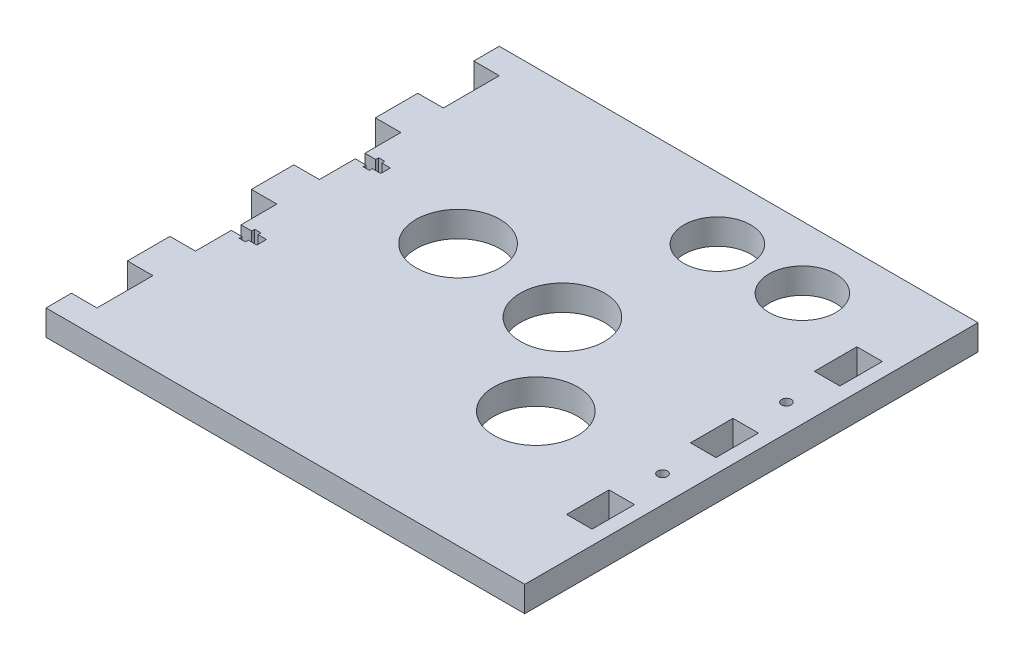
SolidWorks part; units mm, degrees
ref_plane "Front Plane" through (0, 0, 0) normal (0, 0, 1) x (1, 0, 0)
ref_plane "Top Plane" through (0, 0, 0) normal (0, 1, 0) x (1, 0, 0)
ref_plane "Right Plane" through (0, 0, 0) normal (1, 0, 0) x (0, 0, -1)
sketch "Sketch1" plane through (0, 0, 0) normal (0, 1, 0) x (1, 0, 0)
  line L1 (80, -80) -> (-80, -80)
  line L2 (80, -80) -> (80, 80)
  line L3 (80, 80) -> (-80, 80)
  line L4 (-80, -80) -> (-80, 80)
  line L5 (80, -80) -> (-80, 80) construction
  line L6 (80, 80) -> (-80, -80) construction
  point P0 (0, 0)
  dimension "D1" = 160
extrude "Boss-Extrude1" add sketch "Sketch1" along normal blind 9
sketch "Sketch2" plane through (0, 9, 0) normal (0, 1, 0) x (1, 0, 0)
  line L0 (-80, 80) -> (-80, -80) construction
  line L1 (-80, -7.5) -> (-89, -7.5)
  line L2 (-80, -7.5) -> (-80, 7.5)
  line L3 (-80, 7.5) -> (-89, 7.5)
  line L4 (-89, -7.5) -> (-89, 7.5)
  line L5 (-80, 0) -> (0, 0) construction
  line L6 (-80, 80) -> (-80, 51.25) construction
  line L7 (-80, 51.25) -> (-89, 51.25)
  line L8 (-80, 51.25) -> (-80, 36.25)
  line L9 (-80, 36.25) -> (-89, 36.25)
  line L10 (-89, 51.25) -> (-89, 36.25)
  line L11 (-80, -36.25) -> (-89, -36.25)
  line L12 (-80, -36.25) -> (-80, -51.25)
  line L13 (-80, -51.25) -> (-89, -51.25)
  line L14 (-89, -36.25) -> (-89, -51.25)
  line L15 (-80, 36.25) -> (-80, 7.5) construction
  line L16 (-80, -7.5) -> (-80, -36.25) construction
  line L17 (-80, -51.25) -> (-80, -80) construction
  line L19 (-80, 80) -> (-89, 80)
  line L20 (-80, 80) -> (-80, 71)
  line L21 (-80, 71) -> (-89, 71)
  line L22 (-89, 80) -> (-89, 71)
  line L23 (-80, -80) -> (-89, -80)
  line L24 (-80, -80) -> (-80, -71)
  line L25 (-80, -71) -> (-89, -71)
  line L26 (-89, -80) -> (-89, -71)
  dimension "D1" = 9
  dimension "D2" = 15
  dimension "D3" = 9
extrude "Boss-Extrude2" add sketch "Sketch2" against normal up to surface (9 mm away) up to face at (0, 0, 0)
sketch "Sketch3" plane through (0, 9, 0) normal (0, 1, 0) x (1, 0, 0)
  line L1 (75, 51.25) -> (66, 51.25)
  line L2 (75, 51.25) -> (75, 36.25)
  line L3 (75, 36.25) -> (66, 36.25)
  line L4 (66, 51.25) -> (66, 36.25)
  line L5 (-80, 51.25) -> (-89, 51.25) construction
  line L6 (75, 7.5) -> (66, 7.5)
  line L7 (75, 7.5) -> (75, -7.5)
  line L8 (75, -7.5) -> (66, -7.5)
  line L9 (66, 7.5) -> (66, -7.5)
  line L10 (75, -36.25) -> (66, -36.25)
  line L11 (75, -36.25) -> (75, -51.25)
  line L12 (75, -51.25) -> (66, -51.25)
  line L13 (66, -36.25) -> (66, -51.25)
  line L14 (-80, 7.5) -> (-89, 7.5) construction
  line L15 (-89, -7.5) -> (-80, -7.5) construction
  line L16 (-89, -51.25) -> (-80, -51.25) construction
  line L17 (80, -80) -> (80, 80) construction
  line L18 (70.5, 36.25) -> (70.5, 7.5) construction
  line L19 (70.5, 7.5) -> (70.5, -7.5) construction
  line L20 (70.5, -7.5) -> (70.5, -36.25) construction
  line L21 (70.5, -36.25) -> (70.5, -51.25) construction
  line L22 (70.5, -51.25) -> (70.5, -80) construction
  line L23 (-89, -80) -> (80, -80) construction
  line L24 (70.5, 51.25) -> (70.5, 80) construction
  line L25 (80, 80) -> (-89, 80) construction
  circle A0 centre (70.5, 21.875) radius 1.7
  circle A1 centre (70.5, -21.875) radius 1.7
  dimension "D2" = 3.4
  dimension "D1" = 5
extrude "Cut-Extrude1" cut sketch "Sketch3" against normal through all
sketch "Sketch4" plane through (0, 9, 0) normal (0, 1, 0) x (1, 0, 0)
  line L1 (-80, 36.25) -> (-80, 7.5) construction
  line L2 (-89, 51.25) -> (-89, 36.25) construction
  line L3 (-89, 0) -> (0, 0) construction
  line L4 (-89, 7.5) -> (-89, -7.5) construction
  line L5 (-80, -21.875) -> (-71, -21.875) construction
  line L6 (-80, 23.575) -> (-76.2, 23.575)
  line L7 (-80, -23.575) -> (-80, -20.175)
  line L8 (-76.2, -20.175) -> (-80, -20.175)
  line L9 (-76.2, -19.125) -> (-76.2, -20.175)
  line L10 (-74, -19.125) -> (-76.2, -19.125)
  line L11 (-74, -20.175) -> (-74, -19.125)
  line L12 (-71, -20.175) -> (-74, -20.175)
  line L13 (-71, -23.575) -> (-71, -20.175)
  line L14 (-74, -23.575) -> (-71, -23.575)
  line L15 (-74, -24.625) -> (-74, -23.575)
  line L16 (-76.2, -24.625) -> (-74, -24.625)
  line L17 (-76.2, -23.575) -> (-76.2, -24.625)
  line L18 (-80, -23.575) -> (-76.2, -23.575)
  line L20 (-76.2, 23.575) -> (-76.2, 24.625)
  line L21 (-76.2, 24.625) -> (-74, 24.625)
  line L22 (-74, 24.625) -> (-74, 23.575)
  line L23 (-74, 23.575) -> (-71, 23.575)
  line L24 (-71, 23.575) -> (-71, 20.175)
  line L25 (-71, 20.175) -> (-74, 20.175)
  line L26 (-74, 20.175) -> (-74, 19.125)
  line L27 (-74, 19.125) -> (-76.2, 19.125)
  line L28 (-76.2, 19.125) -> (-76.2, 20.175)
  line L29 (-76.2, 20.175) -> (-80, 20.175)
  line L30 (-80, 23.575) -> (-80, 20.175)
  line L31 (-80, 21.875) -> (-71, 21.875) construction
  dimension "D1" = 3.4
  dimension "D2" = 18
  dimension "D3" = 2.2
  dimension "D4" = 5.5
  dimension "D5" = 3
extrude "Cut-Extrude2" cut sketch "Sketch4" against normal through all
sketch "Sketch5" plane through (0, 0, 0) normal (0, -1, 0) x (1, 0, 0)
  line L0 (29.0119, 25.1089) -> (-35.94, -12.3911) construction
  line L1 (29.0119, 25.1089) -> (80, 25.1089) construction
  line L2 (80, 80) -> (80, -80) construction
  line L3 (80, -58) -> (40, -58) construction
  line L4 (40, -58) -> (10, -58) construction
  line L5 (80, -80) -> (-89, -80) construction
  circle A0 centre (29.0119, 25.1089) radius 14.825
  circle A1 centre (5, -8.3013) radius 14.825
  circle A2 centre (-35.94, -12.3911) radius 14.825
  arc A3 (29.0119, 25.1089) -> (-35.94, -12.3911) centre (-20, 35) cw construction
  circle A4 centre (40, -58) radius 11.8
  circle A5 centre (10, -58) radius 11.8
  dimension "D1" = 75
  dimension "D4" = 50
  dimension "D5" = 29.65
  dimension "D9" = 23.6
  dimension "D2" = 20
  dimension "D3" = 150
  dimension "30" = 35
  dimension "D6" = 22
  dimension "D7" = 40
  dimension "D8" = 30
extrude "Cut-Extrude3" cut sketch "Sketch5" against normal through all
